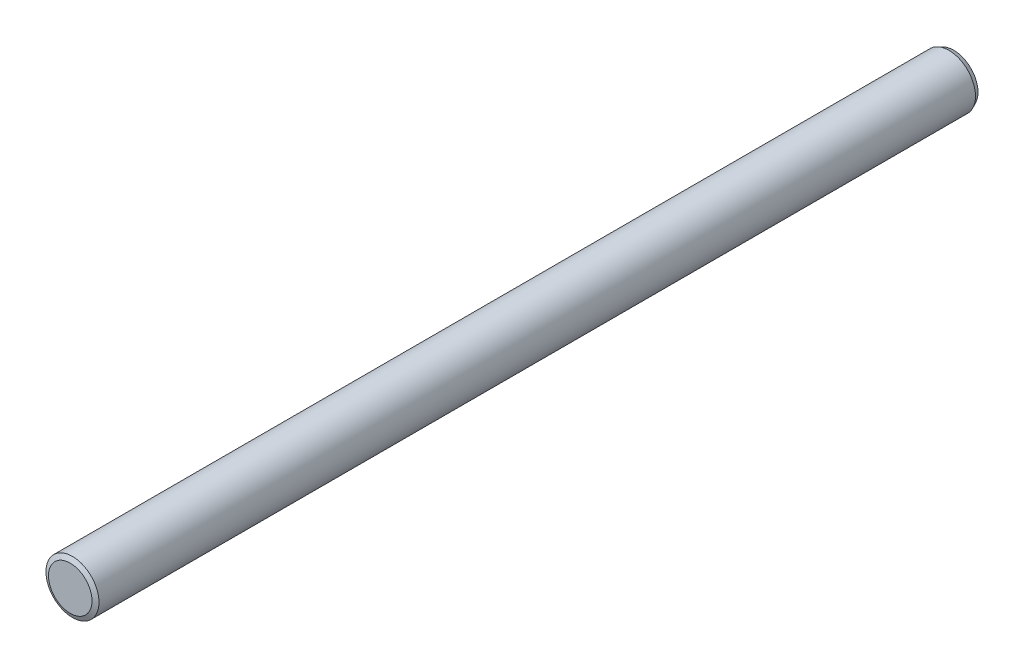
SolidWorks part; units mm, degrees
ref_plane "Front Plane" through (0, 0, 0) normal (0, 0, 1) x (1, 0, 0)
ref_plane "Top Plane" through (0, 0, 0) normal (0, 1, 0) x (1, 0, 0)
ref_plane "Right Plane" through (0, 0, 0) normal (1, 0, 0) x (0, 0, -1)
sketch "Sketch1" plane through (0, 0, 0) normal (0, 0, 1) x (1, 0, 0)
  circle A0 centre (0, 0) radius 3
  dimension "D1" = 6
extrude "Boss-Extrude1" add sketch "Sketch1" along normal mid plane 100
chamfer "Chamfer1" distance 0.25 angle 65 2 edges at (3, 0, -50) (3, 0, 50)
